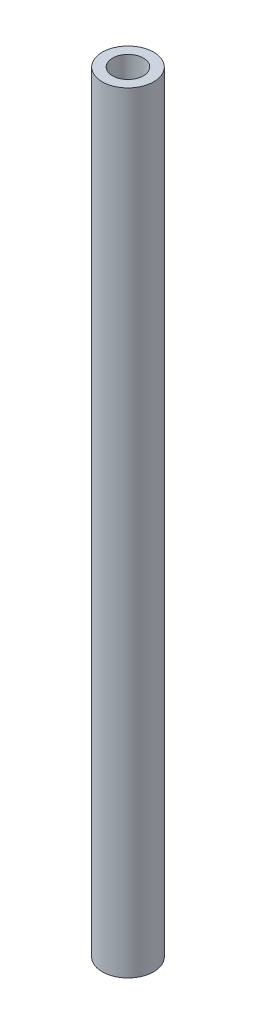
SolidWorks part; units mm, degrees
ref_plane "Front Plane" through (0, 0, 0) normal (0, 0, 1) x (1, 0, 0)
ref_plane "Top Plane" through (0, 0, 0) normal (0, 1, 0) x (1, 0, 0)
ref_plane "Right Plane" through (0, 0, 0) normal (1, 0, 0) x (0, 0, -1)
sketch "Sketch1" plane through (0, 0, 0) normal (0, 1, 0) x (1, 0, 0)
  circle A0 centre (0, 0) radius 2.5
  circle A1 centre (0, 0) radius 1.5
  dimension "D1" = 5
  dimension "D2" = 3
extrude "Boss-Extrude1" add sketch "Sketch1" along normal blind 75
